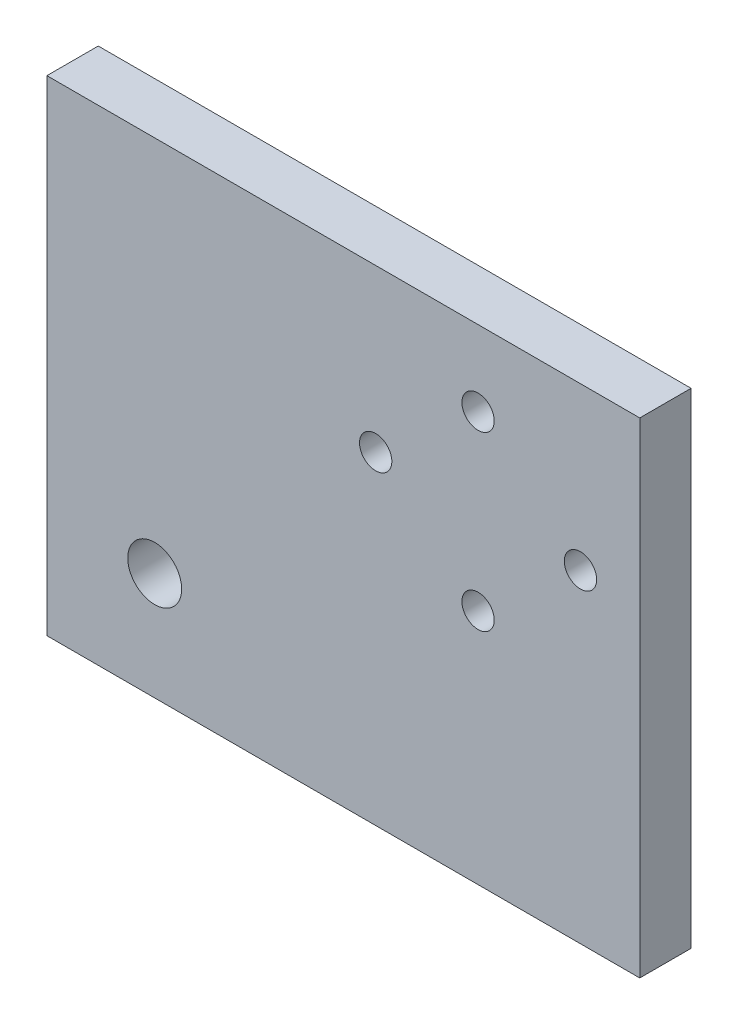
SolidWorks part; units mm, degrees
material "6061-T6 (SS)"
ref_plane "Front Plane" through (0, 0, 0) normal (0, 0, 1) x (1, 0, 0)
ref_plane "Top Plane" through (0, 0, 0) normal (0, 1, 0) x (1, 0, 0)
ref_plane "Right Plane" through (0, 0, 0) normal (1, 0, 0) x (0, 0, -1)
sketch "Sketch1" plane through (0, 0, 0) normal (0, 0, 1) x (1, 0, 0)
  line L0 (30.5, 30) -> (49.5, 30) construction
  line L1 (0, 0) -> (55, 0)
  line L2 (0, 0) -> (0, 45)
  line L3 (0, 45) -> (55, 45)
  line L4 (55, 0) -> (55, 45)
  line L5 (40, 38) -> (40, 22) construction
  circle A0 centre (10, 10) radius 2.5
  circle A1 centre (30.5, 30) radius 1.5
  circle A2 centre (49.5, 30) radius 1.5
  circle A3 centre (40, 38) radius 1.5
  circle A4 centre (40, 22) radius 1.5
  point P11 (40, 30)
  point P12 (40, 30)
  dimension "D7" = 5
  dimension "D5" = 3
  dimension "D6" = 3
  dimension "D1" = 19
  dimension "D2" = 16
  dimension "D3" = 10
  dimension "D4" = 10
  dimension "D8" = 15
  dimension "D9" = 15
  dimension "D10" = 30
  dimension "D11" = 20
extrude "Boss-Extrude1" add sketch "Sketch1" along normal blind 4.7625
